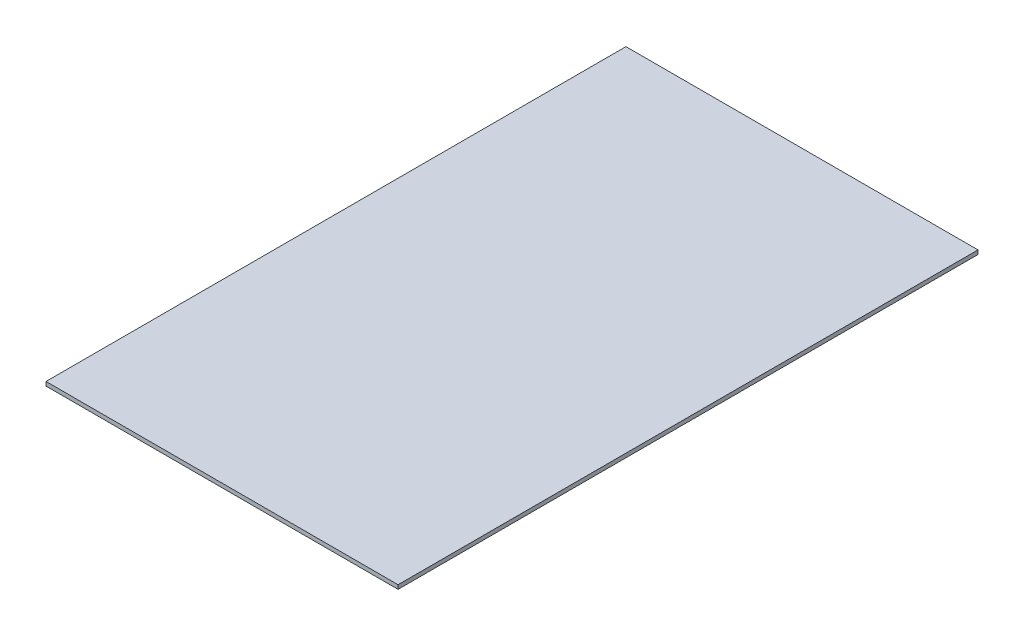
SolidWorks part; units mm, degrees
ref_plane "Front Plane" through (0, 0, 0) normal (0, 0, 1) x (1, 0, 0)
ref_plane "Top Plane" through (0, 0, 0) normal (0, 1, 0) x (1, 0, 0)
ref_plane "Right Plane" through (0, 0, 0) normal (1, 0, 0) x (0, 0, -1)
sketch "Sketch1" plane through (0, 0, 0) normal (0, 0, 1) x (1, 0, 0)
  line L1 (-138.7767, 1.5875) -> (138.7767, 1.5875)
  line L2 (-138.7767, 1.5875) -> (-138.7767, -1.5875)
  line L3 (-138.7767, -1.5875) -> (138.7767, -1.5875)
  line L4 (138.7767, 1.5875) -> (138.7767, -1.5875)
  line L5 (-138.7767, 1.5875) -> (138.7767, -1.5875) construction
  line L6 (-138.7767, -1.5875) -> (138.7767, 1.5875) construction
  point P0 (0, 0)
  dimension "D1" = 3.175
  dimension "D2" = 277.5534
extrude "Boss-Extrude1" add sketch "Sketch1" along normal blind 457.2 contours L1 L4 L3 L2
